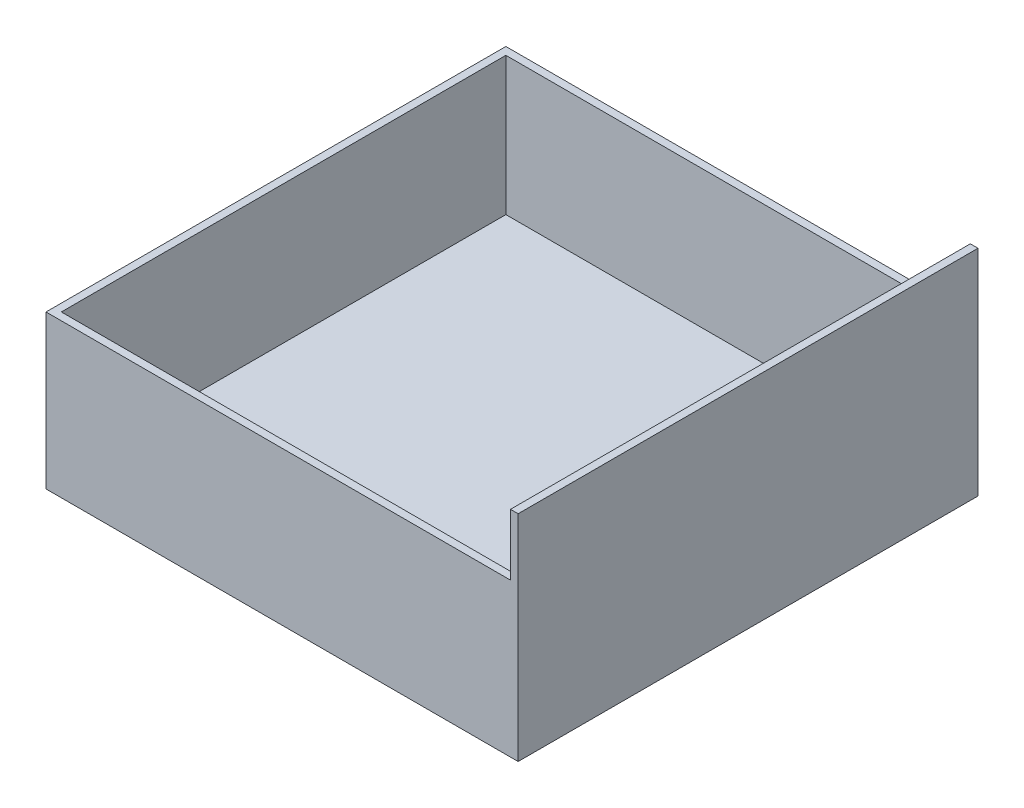
SolidWorks part; units mm, degrees
ref_plane "Front Plane" through (0, 0, 0) normal (0, 0, 1) x (1, 0, 0)
ref_plane "Top Plane" through (0, 0, 0) normal (0, 1, 0) x (1, 0, 0)
ref_plane "Right Plane" through (0, 0, 0) normal (1, 0, 0) x (0, 0, -1)
sketch "Sketch1" plane through (0, 0, 0) normal (0, 1, 0) x (1, 0, 0)
  line L1 (0, 38.1) -> (78.232, 38.1)
  line L2 (0, 38.1) -> (0, -38.1)
  line L3 (0, -38.1) -> (78.232, -38.1)
  line L4 (78.232, 38.1) -> (78.232, -38.1)
  point P5 (0, 0)
  dimension "D1" = 78.232
  dimension "D2" = 76.2
extrude "Boss-Extrude1" add sketch "Sketch1" along normal blind 35.56
sketch "Sketch2" plane through (0, 35.56, 0) normal (0, 1, 0) x (1, 0, 0)
  line L0 (78.232, 38.1) -> (0, 38.1) construction
  line L1 (1.27, 36.83) -> (76.962, 36.83)
  line L2 (1.27, 36.83) -> (1.27, -36.83)
  line L3 (1.27, -36.83) -> (76.962, -36.83)
  line L4 (76.962, 36.83) -> (76.962, -36.83)
  line L5 (0, 38.1) -> (0, -38.1) construction
  line L6 (78.232, -38.1) -> (78.232, 38.1) construction
  line L7 (0, -38.1) -> (78.232, -38.1) construction
  dimension "D1" = 1.27
  dimension "D2" = 1.27
  dimension "D3" = 1.27
  dimension "D4" = 1.27
extrude "Cut-Extrude1" cut sketch "Sketch2" against normal blind 33.02
sketch "Sketch11" plane through (0, 35.56, 0) normal (0, 1, 0) x (1, 0, 0)
  line L0 (76.962, -36.83) -> (76.962, -38.1)
  line L1 (0, -38.1) -> (78.232, -38.1) construction
  line L2 (76.962, 36.83) -> (76.962, 38.1)
  line L3 (78.232, 38.1) -> (0, 38.1) construction
  line L4 (76.962, 38.1) -> (0, 38.1)
  line L5 (0, 38.1) -> (0, -38.1)
  line L6 (0, -38.1) -> (76.962, -38.1)
  line L7 (76.962, -36.83) -> (1.27, -36.83)
  line L8 (1.27, -36.83) -> (1.27, 36.83)
  line L9 (1.27, 36.83) -> (76.962, 36.83)
extrude "Cut-Extrude3" cut sketch "Sketch11" against normal blind 10.16
